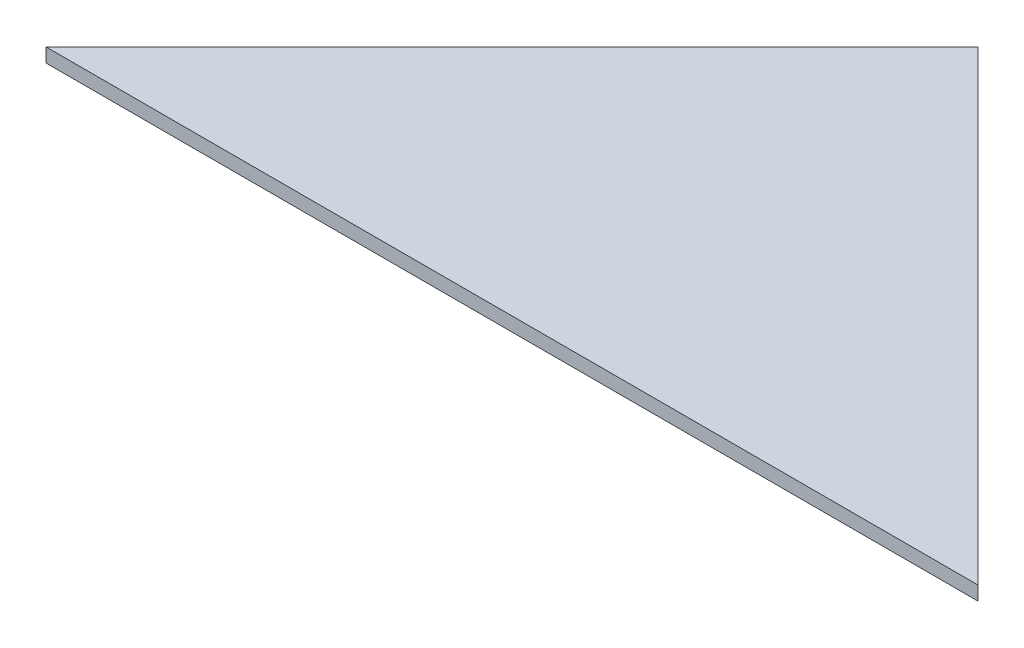
SolidWorks part; units mm, degrees
ref_plane "Front Plane" through (0, 0, 0) normal (0, 0, 1) x (1, 0, 0)
ref_plane "Top Plane" through (0, 0, 0) normal (0, 1, 0) x (1, 0, 0)
ref_plane "Right Plane" through (0, 0, 0) normal (1, 0, 0) x (0, 0, -1)
sketch "Sketch1" plane through (0, 0, 0) normal (0, 1, 0) x (1, 0, 0)
  line L0 (0, 0) -> (-50, -50)
  line L1 (-50, -50) -> (50, -50)
  line L2 (50, -50) -> (0, 0)
  dimension "D1" = 100
extrude "Boss-Extrude1" add sketch "Sketch1" along normal blind 1.5
